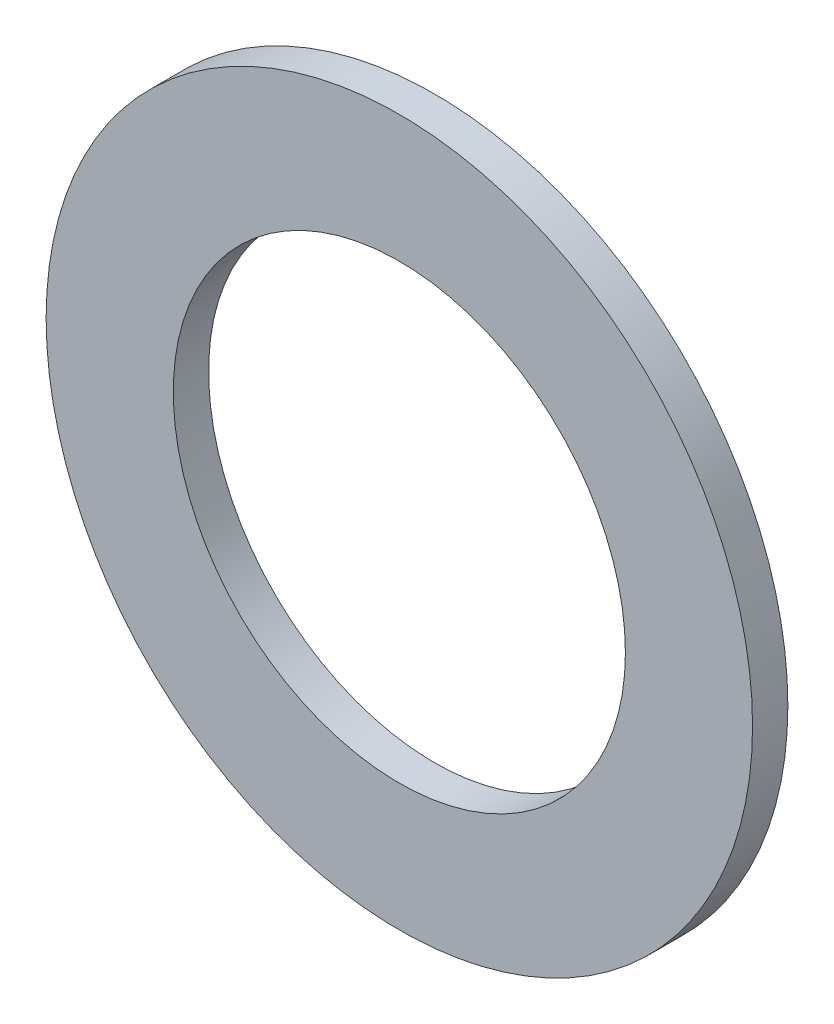
SolidWorks part; units mm, degrees
material "AISI 304"
ref_plane "Front Plane" through (0, 0, 0) normal (0, 0, 1) x (1, 0, 0)
ref_plane "Top Plane" through (0, 0, 0) normal (0, 1, 0) x (1, 0, 0)
ref_plane "Right Plane" through (0, 0, 0) normal (1, 0, 0) x (0, 0, -1)
sketch "Sketch1" plane through (0, 0, 0) normal (0, 0, 1) x (1, 0, 0)
  circle A0 centre (0, 0) radius 12.7
  circle A1 centre (0, 0) radius 19.8438
  dimension "D1" = 25.4
  dimension "D2" = 39.6875
extrude "Boss-Extrude1" add sketch "Sketch1" along normal blind 1.9837
